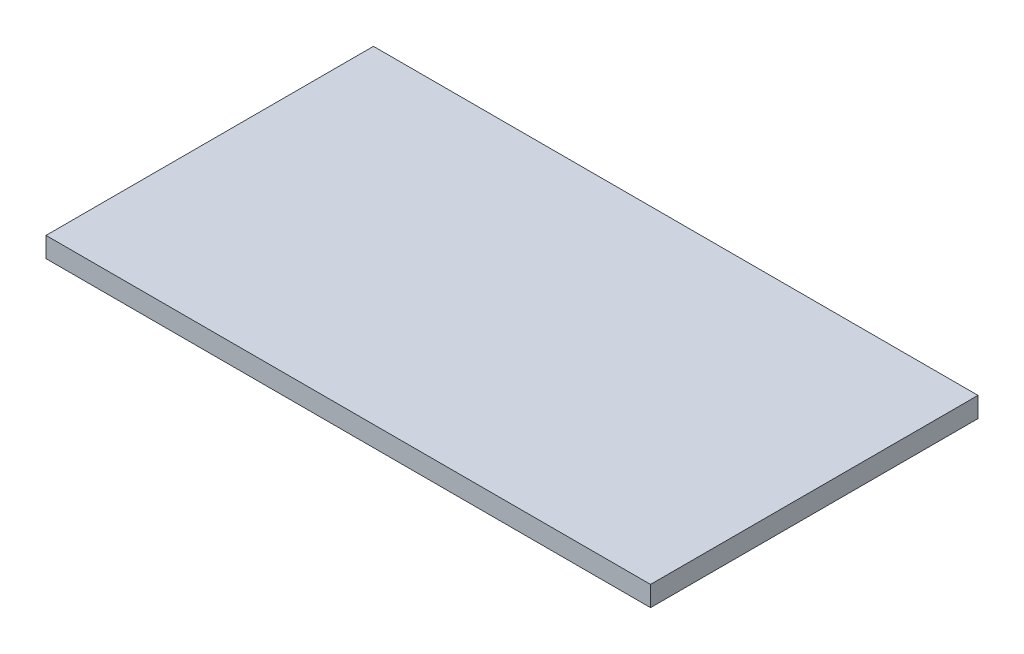
SolidWorks part; units mm, degrees
ref_plane "Front Plane" through (0, 0, 0) normal (0, 0, 1) x (1, 0, 0)
ref_plane "Top Plane" through (0, 0, 0) normal (0, 1, 0) x (1, 0, 0)
ref_plane "Right Plane" through (0, 0, 0) normal (1, 0, 0) x (0, 0, -1)
sketch "Face Plate" plane through (0, 0, 0) normal (0, 1, 0) x (1, 0, 0)
  line L1 (60, -32.5) -> (-60, -32.5)
  line L2 (60, -32.5) -> (60, 32.5)
  line L3 (60, 32.5) -> (-60, 32.5)
  line L4 (-60, -32.5) -> (-60, 32.5)
  line L5 (60, -32.5) -> (-60, 32.5) construction
  line L6 (60, 32.5) -> (-60, -32.5) construction
  point P0 (0, 0)
  dimension "D1" = 120
  dimension "D2" = 65
extrude "Face Plate Ext" add sketch "Face Plate" along normal blind 4
sketch "Pit Fuel" plane through (0, 4, 0) normal (0, 1, 0) x (1, 0, 0)
  line L0 (-60, -32.5) -> (60, -32.5) construction
  line L1 (-60, 32.5) -> (-60, -32.5) construction
  line L2 (-60, -2.5) -> (-15, -2.5) construction
  circle A0 centre (-45, -17.5) radius 6
  circle A1 centre (-15, -17.5) radius 6
  circle A2 centre (15, -17.5) radius 6
  circle A3 centre (45, -17.5) radius 6
  circle A4 centre (-45, 12.5) radius 3.55
  circle A5 centre (45, 12.5) radius 6
  circle A6 centre (15, 12.5) radius 6
  circle A7 centre (-15, 12.5) radius 6
  dimension "D1" = 15
  dimension "D6" = 12
  dimension "D7" = 7.1
  dimension "D2" = 15
  dimension "D3" = 30
  dimension "D4" = 30
  dimension "D5" = 30
  dimension "D8" = 30
  dimension "D9" = 15
  dimension "D10" = 15
